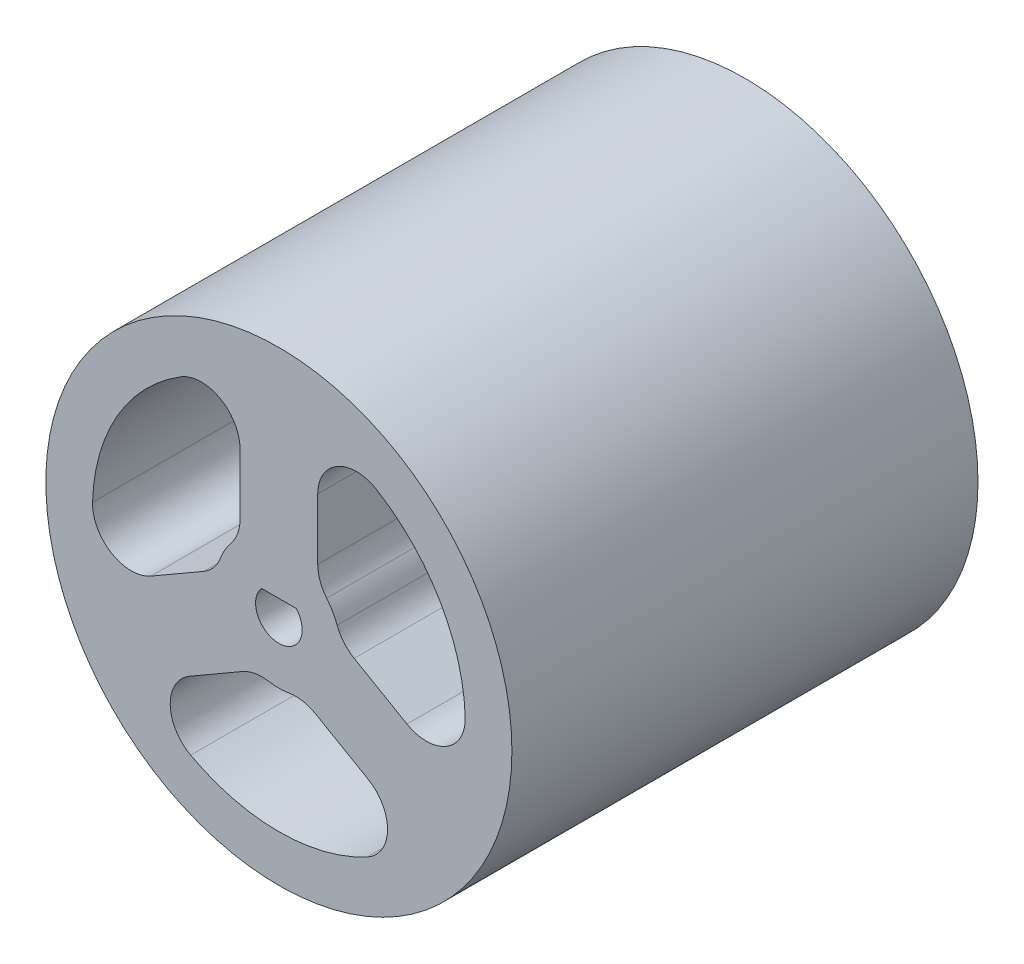
SolidWorks part; units mm, degrees
ref_plane "Płaszczyzna przednia" through (0, 0, 0) normal (0, 0, 1) x (1, 0, 0)
ref_plane "Płaszczyzna górna" through (0, 0, 0) normal (0, 1, 0) x (1, 0, 0)
ref_plane "Płaszczyzna prawa" through (0, 0, 0) normal (1, 0, 0) x (0, 0, -1)
sketch "Szkic1" plane through (0, 0, 0) normal (0, 0, 1) x (1, 0, 0)
  circle A0 centre (0, 0) radius 30
  dimension "D1" = 60
extrude "Dodanie-wyciągnięcie1" add sketch "Szkic1" along normal blind 60
sketch "Szkic3" plane through (0, 0, 60) normal (0, 0, 1) x (1, 0, 0)
  line L0 (-4.174, 2.013) -> (4.0456, 2.013)
  arc A0 (-2.2244, 2.013) -> (2.2244, 2.013) centre (0, 0) ccw
  dimension "D1" = 6
extrude "Wytnij-wyciągnięcie1" cut sketch "Szkic3" against normal blind 13 and the other way through all contours L0 A0
sketch "Szkic4" plane through (0, 0, 60) normal (0, 0, 1) x (1, 0, 0)
  line L0 (-5, 6.245) -> (-5, 23.4734)
  line L1 (5, 6.245) -> (5, 23.4734)
  line L2 (7.9083, 1.2076) -> (22.8286, -7.4066)
  line L3 (2.9083, -7.4526) -> (17.8286, -16.0668)
  line L4 (-2.9083, -7.4526) -> (-17.8286, -16.0668)
  line L5 (-7.9083, 1.2076) -> (-22.8286, -7.4066)
  circle A0 centre (0, 0) radius 8
  circle A1 centre (0, 0) radius 30 construction
  circle A2 centre (0, 0) radius 30
  circle A3 centre (0, 0) radius 24
  point P21 (0, 0)
  dimension "D1" = 16
  dimension "D3" = 10
  dimension "D2" = 6
  dimension "D4" = 3
extrude "Wytnij-wyciągnięcie4" cut sketch "Szkic4" against normal through all contours L0 A3 L5 A0 | L2 A3 L1 A0 | L4 A3 L3 A0
fillet "Zaokrąglenie2" radius 5 12 edges at (2.9083, -7.4526, 30) (-2.9083, -7.4526, 30) (-5, 6.245, 30) (-7.9083, 1.2076, 30) (5, 6.245, 30) (7.9083, 1.2076, 30) (22.8286, -7.4066, 30) (17.8286, -16.0668, 30) (-17.8286, -16.0668, 30) (-22.8286, -7.4066, 30) (5, 23.4734, 30) (-5, 23.4734, 30)
